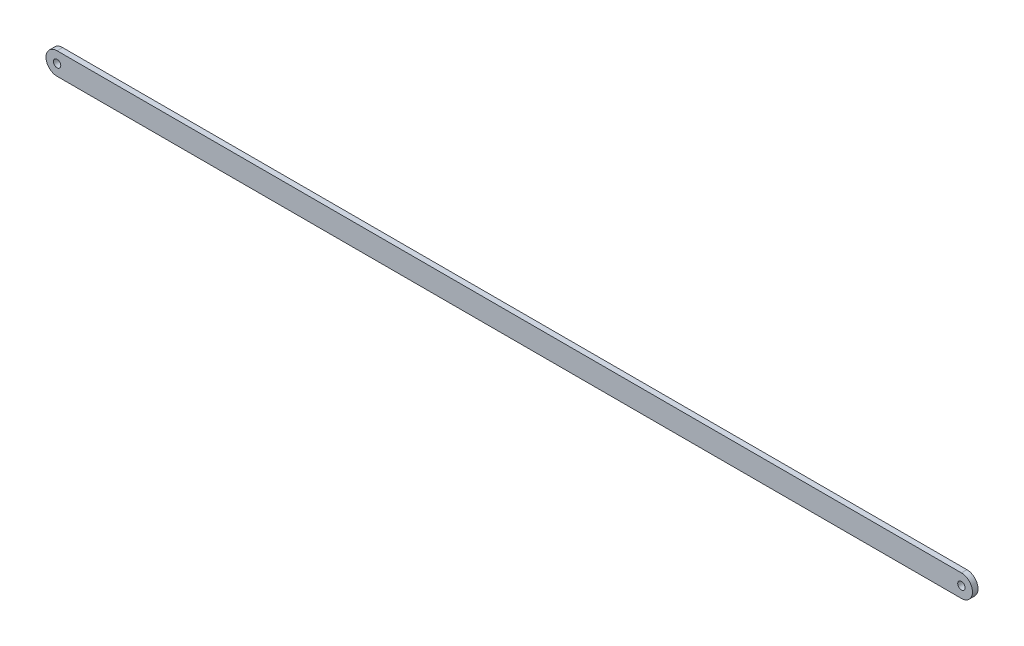
SolidWorks part; units mm, degrees
ref_plane "Front Plane" through (0, 0, 0) normal (0, 0, 1) x (1, 0, 0)
ref_plane "Top Plane" through (0, 0, 0) normal (0, 1, 0) x (1, 0, 0)
ref_plane "Right Plane" through (0, 0, 0) normal (1, 0, 0) x (0, 0, -1)
sketch "Sketch1" plane through (0, 0, 0) normal (0, 0, 1) x (1, 0, 0)
  line L0 (-35.3127, 0) -> (454.6873, 0) construction
  line L1 (-35.3127, 6) -> (454.6873, 6)
  line L2 (-35.3127, -6) -> (454.6873, -6)
  arc A0 (-35.3127, 6) -> (-35.3127, -6) centre (-35.3127, 0) ccw
  arc A1 (454.6873, -6) -> (454.6873, 6) centre (454.6873, 0) ccw
  circle A2 centre (-35.3127, 0) radius 2
  circle A3 centre (454.6873, 0) radius 2
  point P3 (209.6873, 0)
  dimension "D3" = 4
  dimension "D4" = 4
  dimension "D1" = 490
  dimension "D2" = 12
extrude "Boss-Extrude3" add sketch "Sketch1" along normal blind 3
